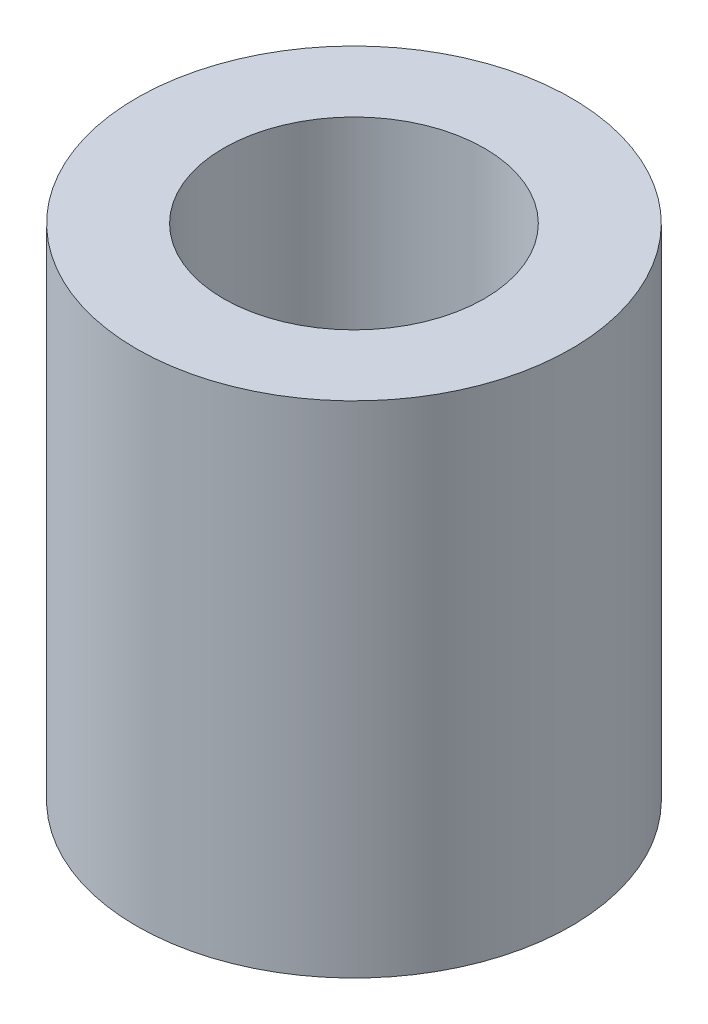
SolidWorks part; units mm, degrees
material "1060 Alloy"
ref_plane "Front Plane" through (0, 0, 0) normal (0, 0, 1) x (1, 0, 0)
ref_plane "Top Plane" through (0, 0, 0) normal (0, 1, 0) x (1, 0, 0)
ref_plane "Right Plane" through (0, 0, 0) normal (1, 0, 0) x (0, 0, -1)
sketch "Sketch1" plane through (0, 0, 0) normal (0, 1, 0) x (1, 0, 0)
  circle A0 centre (0, 0) radius 3
  circle A1 centre (0, 0) radius 5
extrude "Boss-Extrude1" add sketch "Sketch1" along normal blind 11.5
